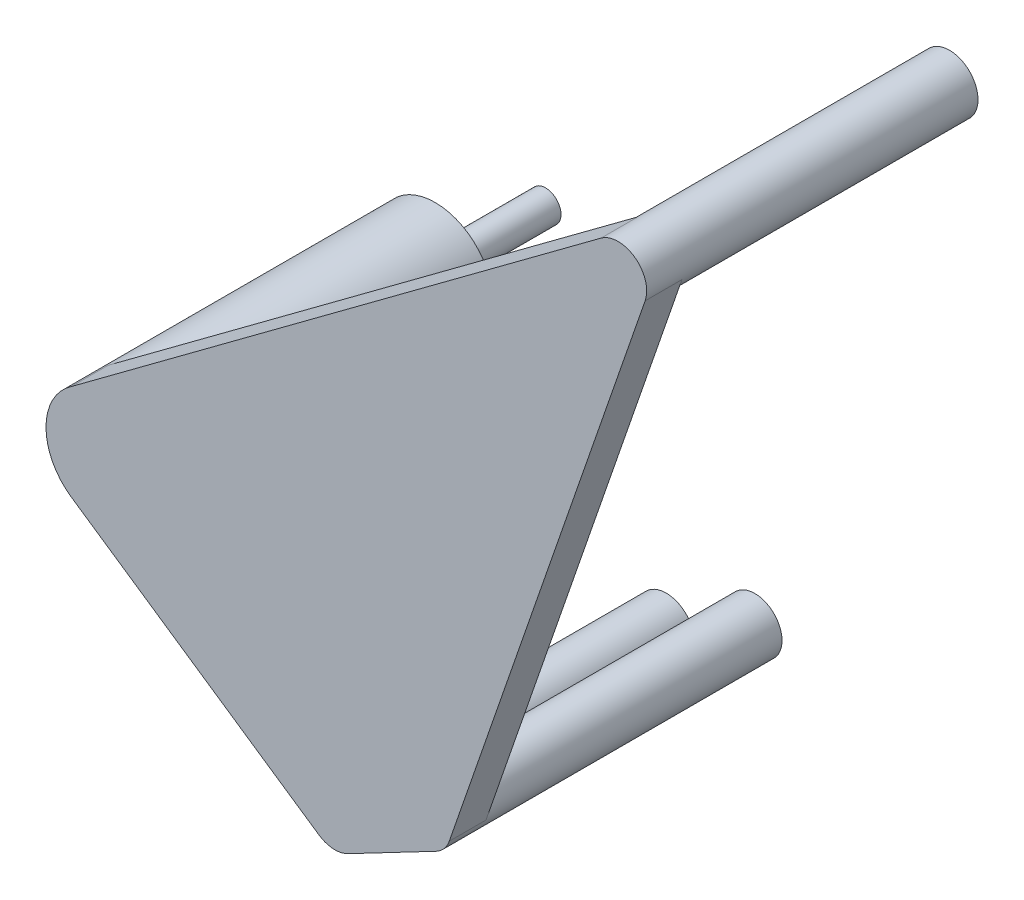
SolidWorks part; units mm, degrees
ref_plane "Front Plane" through (0, 0, 0) normal (0, 0, 1) x (1, 0, 0)
ref_plane "Top Plane" through (0, 0, 0) normal (0, 1, 0) x (1, 0, 0)
ref_plane "Right Plane" through (0, 0, 0) normal (1, 0, 0) x (0, 0, -1)
sketch "Sketch2" plane through (0, 0, 0) normal (0, 0, 1) x (1, 0, 0)
  line L0 (-1395.7664, 232.8715) -> (-1395.7664, 1985.4011) construction
  line L168 (-1647.1874, 301.1556) -> (-1647.1874, 2317.1556) construction
  line L179 (-133.803, 33.5734) -> (-178.7982, 33.5734)
  line L180 (-178.7982, 33.5734) -> (-260.9968, -5.8692)
  line L181 (-260.9968, -5.8692) -> (-257.1598, -33.9699)
  line L182 (-257.1598, -33.9699) -> (-257.1598, -44.8332)
  line L183 (-257.1598, -44.8332) -> (-296.5534, -63.736)
  line L184 (-296.5534, -63.736) -> (-308.6754, -62.5468)
  line L185 (-308.6754, -62.5468) -> (-308.6754, 117.1411)
  line L186 (-308.6754, 117.1411) -> (-300.756, 113.4929)
  line L187 (-300.756, 113.4929) -> (-175.5429, 112.4381)
  line L188 (-175.5429, 112.4381) -> (-168.1865, 115.968)
  line L189 (-168.1865, 115.968) -> (-50.9118, 113.4929)
  line L190 (-50.9118, 113.4929) -> (-50.9118, 115.968)
  line L191 (-50.9118, 115.968) -> (-36.6913, 135.8252)
  line L192 (-36.6913, 135.8252) -> (-31.5738, 138.2808)
  line L193 (-31.5738, 138.2808) -> (-5.8838, 150.608)
  line L194 (-5.8838, 150.608) -> (107.4846, 149.1823)
  line L195 (107.4846, 149.1823) -> (128.3733, 117.1411)
  line L196 (128.3733, 117.1411) -> (145.7874, 117.1411)
  line L197 (145.7874, 117.1411) -> (152.1653, 114.203)
  line L198 (152.1653, 114.203) -> (160.648, 104.4673)
  line L199 (160.648, 104.4673) -> (167.8375, 104.4673)
  line L200 (167.8375, 104.4673) -> (173.3888, 98.9159)
  line L201 (173.3888, 98.9159) -> (173.8274, 95.7036)
  line L202 (173.8274, 95.7036) -> (167.8375, 91.7986)
  line L203 (167.8375, 91.7986) -> (233.2133, 90.9764)
  line L204 (233.2133, 90.9764) -> (240.6201, 87.5643)
  line L205 (240.6201, 87.5643) -> (257.6468, 66.4195)
  line L206 (257.6468, 66.4195) -> (257.6468, 63.8778)
  line L207 (257.6468, 63.8778) -> (249.598, 53.5696)
  line L208 (249.598, 53.5696) -> (248.0214, 45.3458)
  line L209 (248.0214, 45.3458) -> (254.1361, 32.6026)
  line L210 (254.1361, 32.6026) -> (254.7034, 28.4483)
  line L211 (254.7034, 28.4483) -> (250.1892, 27.2972)
  line L212 (250.1892, 27.2972) -> (244.5367, 15.027)
  line L213 (244.5367, 15.027) -> (242.0682, 12.5585)
  line L214 (242.0682, 12.5585) -> (239.1826, 12.5585)
  line L215 (239.1826, 12.5585) -> (239.1826, -0.2727)
  line L216 (239.1826, -0.2727) -> (189.2936, -18.7617)
  line L217 (189.2936, -18.7617) -> (184.6378, -28.8683)
  line L218 (184.6378, -28.8683) -> (165.5344, -32.0319)
  line L219 (165.5344, -32.0319) -> (157.3487, -26.1697)
  line L220 (157.3487, -26.1697) -> (147.9104, -4.5175)
  line L221 (147.9104, -4.5175) -> (132.6552, -4.1955)
  line L222 (132.6552, -4.1955) -> (128.8477, -9.0718)
  line L223 (128.8477, -9.0718) -> (109.604, -9.5172)
  line L224 (109.604, -9.5172) -> (106.7342, -11.6012)
  line L225 (106.7342, -11.6012) -> (21.3384, -11.6012)
  line L226 (21.3384, -11.6012) -> (21.3384, -19.9195)
  line L227 (21.3384, -19.9195) -> (19.8686, -24.822)
  line L228 (19.8686, -24.822) -> (16.8589, -24.822)
  line L229 (16.8589, -24.822) -> (14.5306, -21.6157)
  line L230 (14.5306, -21.6157) -> (13.9192, -13.6231)
  line L231 (13.9192, -13.6231) -> (13.9192, -11.1734)
  line L232 (13.9192, -11.1734) -> (12.3931, -9.0718)
  line L233 (12.3931, -9.0718) -> (-7.8979, -9.5414)
  line L234 (-7.8979, -9.5414) -> (-12.5558, -4.1955)
  line L235 (-12.5558, -4.1955) -> (-14.2294, -5.6537)
  line L236 (-14.2294, -5.6537) -> (-28.9642, -34.3324)
  line L237 (-28.9642, -34.3324) -> (-26.5892, -51.7262)
  line L238 (-26.5892, -51.7262) -> (-44.481, -92.8698)
  line L239 (-44.481, -92.8698) -> (-47.4697, -95.0401)
  line L240 (-47.4697, -95.0401) -> (-52.7041, -95.0401)
  line L241 (-52.7041, -95.0401) -> (-67.0585, -88.798)
  line L242 (-67.0585, -88.798) -> (-69.5077, -87.5395)
  line L243 (-69.5077, -87.5395) -> (-72.2263, -83.3696)
  line L244 (-72.2263, -83.3696) -> (-94.1204, -75.2618)
  line L245 (-94.1204, -75.2618) -> (-95.7689, -76.3365)
  line L246 (-95.7689, -76.3365) -> (-98.8583, -75.7442)
  line L247 (-98.8583, -75.7442) -> (-110.0115, -70.0138)
  line L248 (-110.0115, -70.0138) -> (-111.1609, -67.377)
  line L249 (-111.1609, -67.377) -> (-131.1287, -67.8392)
  line L250 (-131.1287, -67.8392) -> (-135.99, -66.3816)
  line L251 (-135.99, -66.3816) -> (-145.0882, -55.083)
  line L252 (-145.0882, -55.083) -> (-144.4774, -48.858)
  line L253 (-144.4774, -48.858) -> (-141.4827, -43.0293)
  line L254 (-141.4827, -43.0293) -> (-142.9801, -39.5942)
  line L255 (-142.9801, -39.5942) -> (-142.9801, -34.3324)
  line L256 (-142.9801, -34.3324) -> (-142.3227, -27.6314)
  line L257 (-142.3227, -27.6314) -> (-141.8897, -23.2189)
  line L258 (-141.8897, -23.2189) -> (-138.5197, -15.9033)
  line L259 (-138.5197, -15.9033) -> (-134.3792, -9.0718)
  line L260 (-134.3792, -9.0718) -> (-129.3025, -2.5702)
  line L261 (-129.3025, -2.5702) -> (-125.2312, 0.9771)
  line L262 (-125.2312, 0.9771) -> (-121.8226, 3.1993)
  line L263 (-121.8226, 3.1993) -> (-120.8136, 4.4558)
  line L264 (-120.8136, 4.4558) -> (-119.6766, 5.8716)
  line L265 (-119.6766, 5.8716) -> (-118.9997, 7.3526)
  line L266 (-118.9997, 7.3526) -> (-118.2822, 9.153)
  line L267 (-118.2822, 9.153) -> (-118.0908, 11.3455)
  line L268 (-118.0908, 11.3455) -> (-117.7885, 14.807)
  line L269 (-117.7885, 14.807) -> (-117.7885, 18.2254)
  line L270 (-117.7885, 18.2254) -> (-117.9396, 19.8564)
  line L271 (-117.9396, 19.8564) -> (-118.6819, 22.0613)
  line L272 (-118.6819, 22.0613) -> (-118.9087, 22.7352)
  line L273 (-120.8136, 24.9682) -> (-118.9087, 22.7352)
  line L274 (-120.8136, 24.9682) -> (-123.5044, 27.659)
  line L275 (-123.5044, 27.659) -> (-128.0489, 30.1279)
  line L276 (-128.0489, 30.1279) -> (-132.0963, 32.3267)
  line L277 (-132.0963, 32.3267) -> (-133.803, 33.5734)
  line L278 (-12.5558, 106.4159) -> (-12.5558, 127.7793)
  line L279 (-12.5558, 127.7793) -> (-10.3407, 130.812)
  line L280 (-10.3407, 130.812) -> (-2.8432, 132.6568)
  line L281 (-2.8432, 132.6568) -> (3.2533, 133.4505)
  line L282 (3.2533, 133.4505) -> (8.705, 132.4078)
  line L283 (8.705, 132.4078) -> (13.5161, 130.3225)
  line L284 (13.5161, 130.3225) -> (14.5306, 129.7875)
  line L285 (14.5306, 129.7875) -> (18.1825, 129.5615)
  line L286 (18.1825, 129.5615) -> (22.2841, 131.0736)
  line L287 (22.2841, 131.0736) -> (24.7526, 131.7344)
  line L288 (24.7526, 131.7344) -> (27.9259, 132.1475)
  line L289 (27.9259, 132.1475) -> (29.9862, 131.9409)
  line L290 (29.9862, 131.9409) -> (33.3385, 131.1803)
  line L291 (33.3385, 131.1803) -> (37.6837, 128.8886)
  line L292 (37.6837, 128.8886) -> (40.3887, 128.8886)
  line L293 (40.3887, 128.8886) -> (41.2282, 128.8886)
  line L294 (41.2282, 128.8886) -> (42.5759, 129.7875)
  line L295 (42.5759, 129.7875) -> (45.9586, 131.1803)
  line L296 (45.9586, 131.1803) -> (49.4, 131.5606)
  line L297 (49.4, 131.5606) -> (54.1505, 131.5606)
  line L298 (54.1505, 131.5606) -> (60.6434, 128.5787)
  line L299 (60.6434, 128.5787) -> (63.484, 128.2939)
  line L300 (63.484, 128.2939) -> (67.3904, 130.0697)
  line L301 (67.3904, 130.0697) -> (71.1014, 130.9828)
  line L302 (71.1014, 130.9828) -> (76.1342, 131.539)
  line L303 (76.1342, 131.539) -> (79.4118, 131.7344)
  line L304 (79.4118, 131.7344) -> (85.6851, 129.7875)
  line L305 (85.6851, 129.7875) -> (91.3626, 126.7931)
  line L306 (91.3626, 126.7931) -> (96.0039, 114.203)
  line L307 (96.0039, 114.203) -> (96.5933, 108.8694)
  line L308 (96.5933, 108.8694) -> (89.9928, 104.4673)
  line L309 (89.9928, 104.4673) -> (76.5787, 104.4673)
  line L310 (76.5787, 104.4673) -> (71.5086, 102.1625)
  line L311 (71.5086, 102.1625) -> (69.7451, 106.9465)
  line L312 (69.7451, 106.9465) -> (-8.9538, 110.8324)
  line L313 (-8.9538, 110.8324) -> (-12.5558, 106.4159)
  line L314 (-60.9482, -11.1734) -> (-49.9855, -15.9033)
  line L315 (-49.9855, -15.9033) -> (-46.7509, -18.5414)
  line L316 (-46.7509, -18.5414) -> (-46.2015, -19.8276)
  line L317 (-46.2015, -19.8276) -> (-45.64, -22.1577)
  line L318 (-45.64, -22.1577) -> (-45.3873, -24.822)
  line L319 (-45.3873, -24.822) -> (-45.7804, -27.267)
  line L320 (-45.7804, -27.267) -> (-46.7509, -29.0918)
  line L321 (-46.7509, -29.0918) -> (-48.5488, -31.2962)
  line L322 (-48.5488, -31.2962) -> (-50.9118, -32.9458)
  line L323 (-50.9118, -32.9458) -> (-53.2361, -33.5935)
  line L324 (-53.2361, -33.5935) -> (-54.2647, -34.0329)
  line L325 (-54.2647, -34.0329) -> (-55.4669, -35.2182)
  line L326 (-55.4669, -35.2182) -> (-57.0208, -38.1397)
  line L327 (-57.0208, -38.1397) -> (-57.0208, -40.6689)
  line L328 (-57.0208, -40.6689) -> (-56.1372, -41.7577)
  line L329 (-56.1372, -41.7577) -> (-55.3169, -42.7683)
  line L330 (-55.3169, -42.7683) -> (-54.5882, -44.4739)
  line L331 (-54.5882, -44.4739) -> (-54.4752, -47.7702)
  line L332 (-54.4752, -47.7702) -> (-55.2128, -50.7833)
  line L333 (-55.2128, -50.7833) -> (-57.3319, -54.2224)
  line L334 (-57.3319, -54.2224) -> (-59.8885, -59.0289)
  line L335 (-59.8885, -59.0289) -> (-61.4713, -62.0047)
  line L336 (-61.4713, -62.0047) -> (-63.4405, -64.2241)
  line L337 (-63.4405, -64.2241) -> (-67.2393, -66.8762)
  line L338 (-67.2393, -66.8762) -> (-70.4172, -68.6919)
  line L339 (-70.4172, -68.6919) -> (-78.8872, -66.3816)
  line L340 (-78.8872, -66.3816) -> (-86.5217, -64.0024)
  line L341 (-86.5217, -64.0024) -> (-88.6105, -59.6115)
  line L342 (-88.6105, -59.6115) -> (-88.6105, -57.485)
  line L343 (-88.6105, -57.485) -> (-90.1039, -56.16)
  line L344 (-90.1039, -56.16) -> (-90.1039, -54.5542)
  line L345 (-90.1039, -54.5542) -> (-82.6486, -24.0985)
  line L346 (-119.8921, 4.8168) -> (-73.8388, -14.1836) construction
  line L347 (-82.6486, -24.0985) -> (-78.2974, -19.9195)
  line L348 (-78.2974, -19.9195) -> (-76.1757, -21.0481)
  line L349 (-76.1757, -21.0481) -> (-75.3081, -23.8876)
  line L350 (-75.3081, -23.8876) -> (-69.5998, -26.0704)
  line L351 (-69.5998, -26.0704) -> (-66.4787, -23.5373)
  line L352 (-66.4787, -23.5373) -> (-71.3875, -17.4893)
  line L353 (-71.3875, -17.4893) -> (-68.8849, -13.428)
  line L354 (-68.8849, -13.428) -> (-67.0585, -13.1313)
  line L355 (-67.0585, -13.1313) -> (-62.6304, -10.8786)
  line L356 (-62.6304, -10.8786) -> (-60.9482, -11.1734)
  circle A0 centre (-135.99, 14.807) radius 15
  circle A1 centre (-53.2361, -23.5373) radius 7.0481
  circle A2 centre (-2.8432, 123.138) radius 7.405
  circle A3 centre (-76.1757, -35.2182) radius 7.3431
  point P187 (-30.651, -63.3459)
  point P188 (0, 0)
  point P193 (-134.3792, 14.807)
  point P194 (-78.8872, -42.7683)
  point P195 (-54.2647, -22.1577)
  point P196 (-2.8432, 123.138)
  point P197 (-53.2361, -23.5373)
  point P198 (-76.1757, -36.6232)
  point P199 (-77.0668, -36.1386)
  point P200 (-76.1757, -35.2182)
  dimension "D1" = 30
extrude "Boss-Extrude5" add sketch "Sketch2" along normal mid plane 81.026 contours A0 | A3 | A1 | A2
sketch "Sketch6" plane through (0, 0, 40.513) normal (0, 0, 1) x (1, 0, 0)
  line L0 (-80.3108, -41.2863) -> (-144.4368, 2.4113)
  line L1 (-144.4368, 27.2026) -> (-7.2583, 129.0829)
  line L2 (-72.7689, -41.7232) -> (-49.9662, -29.7809)
  line L3 (-46.5758, -25.8427) -> (4.1545, 120.7158)
  circle A0 centre (-135.99, 14.807) radius 15
  circle A1 centre (-76.1757, -35.2182) radius 7.3431
  circle A2 centre (-53.2361, -23.5373) radius 7.0481
  circle A3 centre (-2.8432, 123.138) radius 7.405
  circle M1 centre (-135.99, 14.807) radius 15
extrude "Boss-Extrude6" add sketch "Sketch6" along normal mid plane 9.525 contours A3 L1 L0 A1 L2 A2 L3 M1 | M1 | A1 | A2 | A3 L2
ref_plane "Plane1" through (-46.5758, -25.8427, 35.7505) normal (0.3271, 0.945, 0) x (0.945, -0.3271, 0)
sketch "Sketch9" plane through (0, 0, -40.513) normal (0, 0, -1) x (-1, 0, 0)
  circle A0 centre (53.2361, -23.5373) radius 1.27
  circle A1 centre (76.1757, -35.2182) radius 1.27
  circle A3 centre (2.8432, 123.138) radius 1.27
  dimension "D1" = 2.54
  dimension "D3" = 2.54
  dimension "D4" = 2.54
extrude "Cut-Extrude2" cut sketch "Sketch9" against normal blind 9.525
sketch "Sketch10" plane through (0, 0, -40.513) normal (0, 0, -1) x (-1, 0, 0)
  circle A0 centre (135.99, 14.807) radius 4
  dimension "D1" = 8
extrude "Boss-Extrude7" add sketch "Sketch10" along normal blind 28.575
